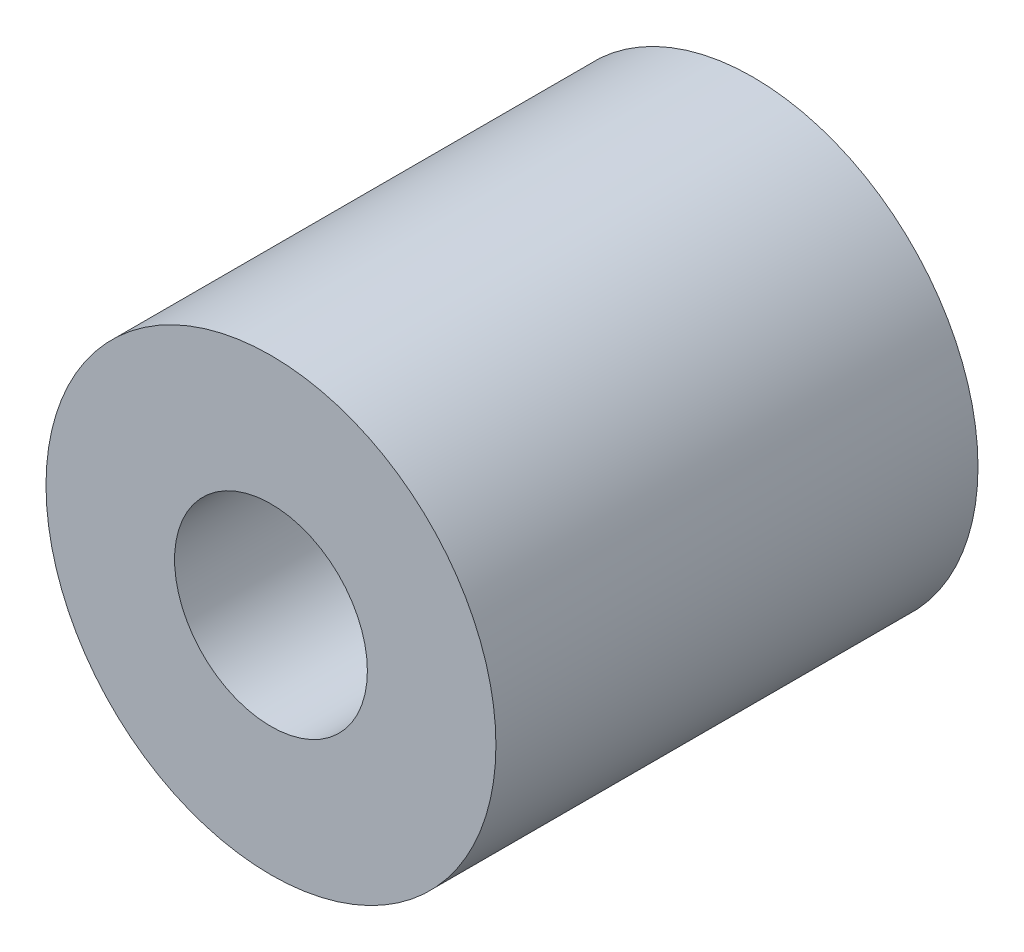
SolidWorks part; units mm, degrees
ref_plane "Спереди" through (0, 0, 0) normal (0, 0, 1) x (1, 0, 0)
ref_plane "Сверху" through (0, 0, 0) normal (0, 1, 0) x (1, 0, 0)
ref_plane "Справа" through (0, 0, 0) normal (1, 0, 0) x (0, 0, -1)
sketch "Эскиз1" plane through (0, 0, 0) normal (0, 0, 1) x (1, 0, 0)
  circle A0 centre (0, 0) radius 3
  circle A1 centre (0, 0) radius 7
extrude "Вытянуть1" add sketch "Эскиз1" along normal blind 15
